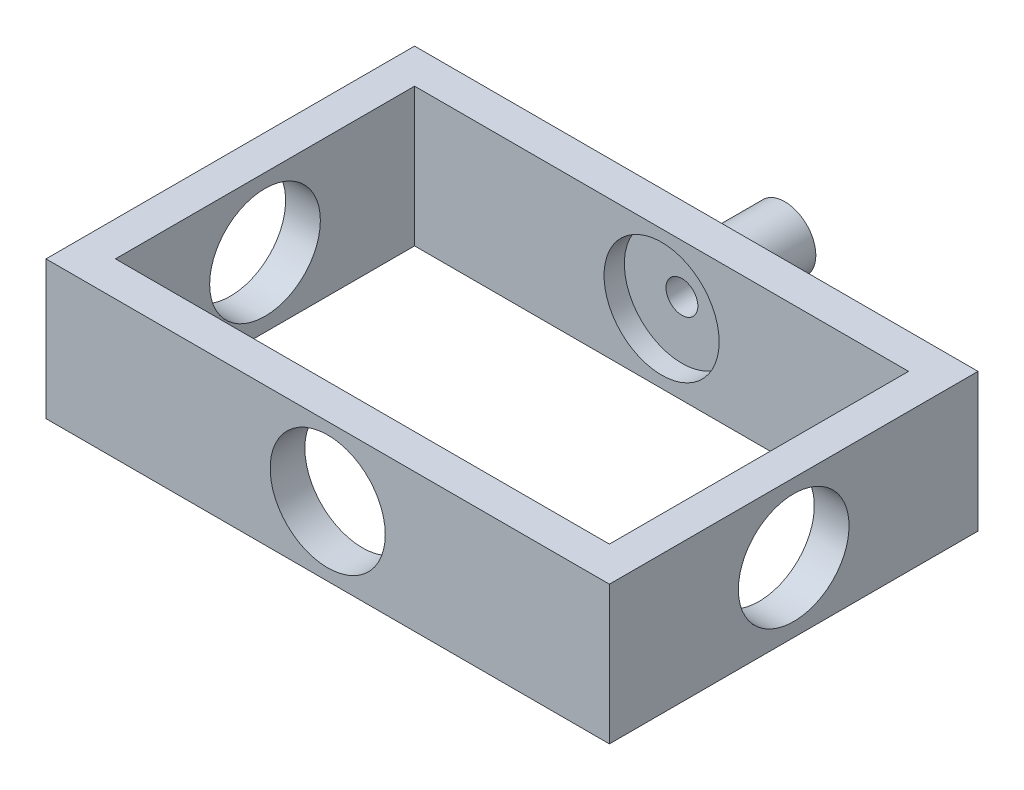
SolidWorks part; units mm, degrees
ref_plane "Front Plane" through (0, 0, 0) normal (0, 0, 1) x (1, 0, 0)
ref_plane "Top Plane" through (0, 0, 0) normal (0, 1, 0) x (1, 0, 0)
ref_plane "Right Plane" through (0, 0, 0) normal (1, 0, 0) x (0, 0, -1)
sketch "Sketch1" plane through (0, 0, 0) normal (0, 1, 0) x (1, 0, 0)
  line L1 (-16.1608, 10.5727) -> (16.1607, 10.5727)
  line L2 (-16.1608, 10.5727) -> (-16.1607, -10.5728)
  line L3 (-16.1607, -10.5728) -> (16.1607, -10.5728)
  line L4 (16.1607, 10.5727) -> (16.1607, -10.5728)
  line L5 (-16.1608, 10.5727) -> (16.1607, -10.5728) construction
  line L6 (-16.1607, -10.5728) -> (16.1607, 10.5727) construction
  line L7 (-14.1694, 8.5814) -> (14.1694, 8.5814)
  line L8 (-14.1694, 8.5814) -> (-14.1694, -8.5814)
  line L9 (-14.1694, -8.5814) -> (14.1694, -8.5814)
  line L10 (14.1694, 8.5814) -> (14.1694, -8.5814)
  line L11 (-14.1694, 8.5814) -> (14.1694, -8.5814) construction
  line L12 (-14.1694, -8.5814) -> (14.1694, 8.5814) construction
  point P0 (0, 0)
  point P5 (0, 0)
extrude "Boss-Extrude1" add sketch "Sketch1" along normal blind 7.9375
sketch "Sketch2" plane through (-16.1608, 0, 0) normal (-1, 0, 0) x (0, 0, 1)
  circle A0 centre (0, 3.9688) radius 3.175
extrude "Cut-Extrude1" cut sketch "Sketch2" against normal blind 37.1475
sketch "Sketch3" plane through (0, 0, 10.5728) normal (0, 0, 1) x (1, 0, 0)
  circle A0 centre (0, 3.9688) radius 3.302
extrude "Cut-Extrude2" cut sketch "Sketch3" against normal blind 20.32
sketch "Sketch4" plane through (0, 0, -10.5727) normal (0, 0, -1) x (-1, 0, 0)
  circle A1 centre (0, 3.9688) radius 1.778
extrude "Boss-Extrude3" add sketch "Sketch4" along normal blind 5.08
sketch "Sketch6" plane through (0, 0, -15.6527) normal (0, 0, -1) x (-1, 0, 0)
  circle A0 centre (0, 3.9688) radius 0.9144
extrude "Cut-Extrude3" cut sketch "Sketch6" against normal blind 10.922
